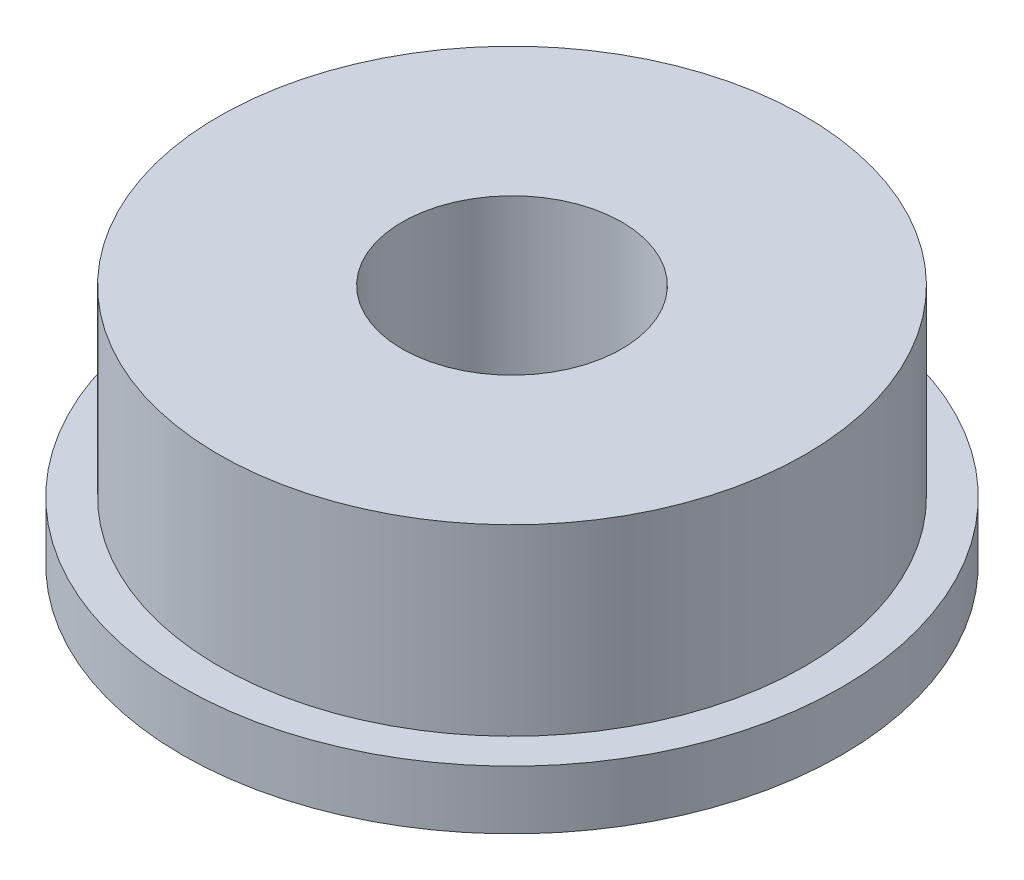
SolidWorks part; units mm, degrees
ref_plane "Front Plane" through (0, 0, 0) normal (0, 0, 1) x (1, 0, 0)
ref_plane "Top Plane" through (0, 0, 0) normal (0, 1, 0) x (1, 0, 0)
ref_plane "Right Plane" through (0, 0, 0) normal (1, 0, 0) x (0, 0, -1)
sketch "Sketch1" plane through (0, 0, 0) normal (0, 1, 0) x (1, 0, 0)
  circle A0 centre (0, 0) radius 4.5
  dimension "D1" = 9
extrude "Boss-Extrude1" add sketch "Sketch1" along normal blind 0.8
ref_plane "Plane1" through (0, 0.8, 0) normal (0, -1, 0) x (-1, 0, 0)
sketch "Sketch2" plane through (0, 0.8, 0) normal (0, -1, 0) x (-1, 0, 0)
  circle A0 centre (0, 0) radius 4
  dimension "D1" = 8
extrude "Boss-Extrude2" add sketch "Sketch2" against normal blind 2.5
sketch "Sketch3" plane through (0, 0, 0) normal (0, 1, 0) x (1, 0, 0)
  circle A0 centre (0, 0) radius 1.5
  dimension "D1" = 3
extrude "Cut-Extrude1" cut sketch "Sketch3" along normal blind 12.5
